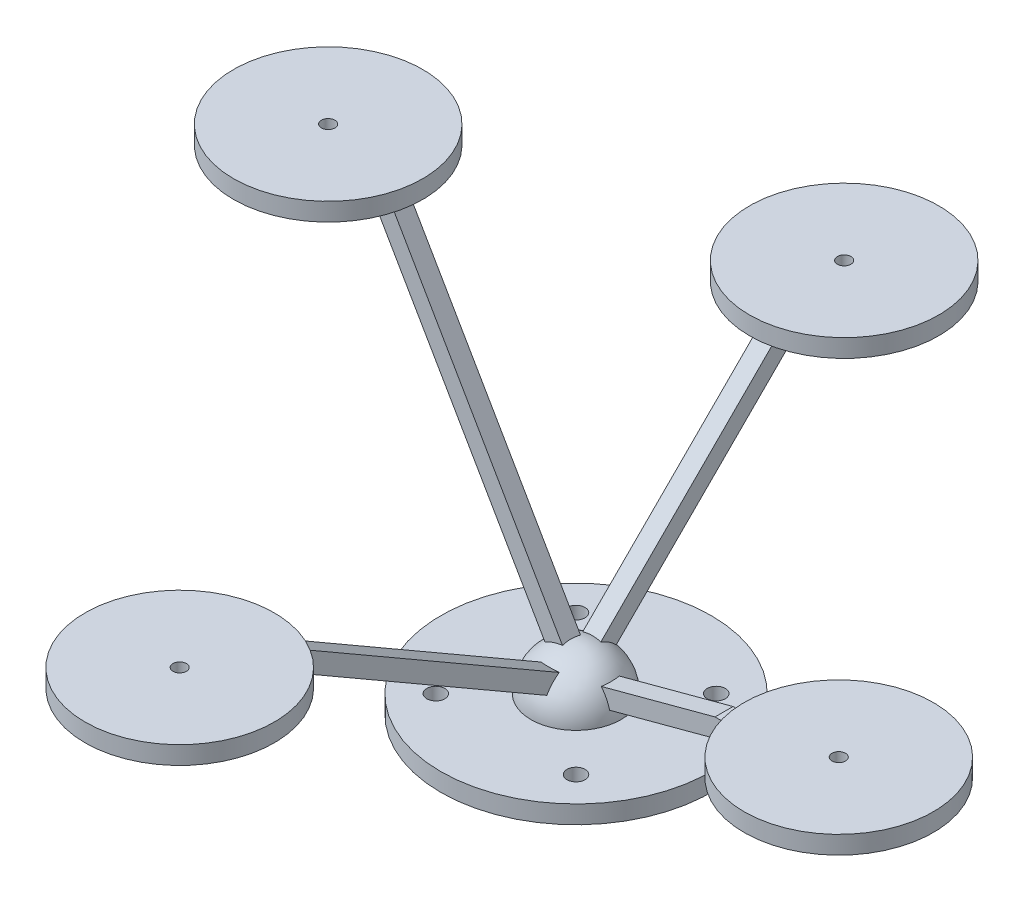
SolidWorks part; units mm, degrees
ref_plane "前视基准面" through (0, 0, 0) normal (0, 0, 1) x (1, 0, 0)
ref_plane "上视基准面" through (0, 0, 0) normal (0, 1, 0) x (1, 0, 0)
ref_plane "右视基准面" through (0, 0, 0) normal (1, 0, 0) x (0, 0, -1)
sketch "草图1" plane through (0, 0, 0) normal (0, 1, 0) x (1, 0, 0)
  line L0 (-23.4221, 0) -> (25.8766, 0) construction
  line L1 (0, 26.1921) -> (0, -25.0701) construction
  line L2 (-18.9498, 18.9498) -> (18.8862, -18.8862) construction
  line L3 (18.9424, 18.9424) -> (-20.2044, -20.2044) construction
  circle A0 centre (0, 0) radius 15
  circle A1 centre (0, 0) radius 11 construction
  circle A2 centre (7.7782, 7.7782) radius 1
  circle A3 centre (-7.7782, 7.7782) radius 1
  circle A4 centre (-7.7782, -7.7782) radius 1
  circle A5 centre (7.7782, -7.7782) radius 1
  dimension "D1" = 30
  dimension "D4" = 22
  dimension "D5" = 2
  dimension "D2" = 45
  dimension "D3" = 45
extrude "凸台-拉伸1" add sketch "草图1" along normal blind 2
sketch "草图2" plane through (0, 0, 0) normal (1, 0, 0) x (0, 0, -1)
  line L0 (0, 2) -> (0, 7)
  line L1 (15, 2) -> (-15, 2) construction
  line L2 (0, 2) -> (5, 2)
  arc A0 (0, 7) -> (5, 2) centre (0, 2) cw
  dimension "D1" = 5
revolve "旋转1" add sketch "草图2" angle 360 about L0
sketch "草图3" plane through (0, 0, 0) normal (0, 0, 1) x (1, 0, 0)
  line L0 (0, 2) -> (0, 9.7216) construction
  line L1 (15, 2) -> (-15, 2) construction
  line L2 (0, 2) -> (24.1481, 8.4705)
  line L3 (8.7782, 2) -> (6.7782, 2) construction
  line L4 (0, 4.0706) -> (16.4207, 8.4705)
  line L6 (16.4207, 8.4705) -> (24.1481, 8.4705)
  line L7 (0, 2) -> (-22.5, 40.9711)
  line L8 (-20.1906, 40.9711) -> (0, 6)
  line L9 (0, 6) -> (0, 4.0706)
  line L10 (-22.5, 40.9711) -> (-20.1906, 40.9711)
  dimension "D1" = 15
  dimension "D2" = 25
  dimension "D3" = 2
  dimension "D4" = 60
  dimension "D5" = 45
  dimension "D6" = 2
extrude "凸台-拉伸2" add sketch "草图3" along normal mid plane 2
sketch "草图4" plane through (0, 8.4705, 0) normal (0, 1, 0) x (1, 0, 0)
  line L0 (24.1481, -1) -> (24.1481, 1) construction
  circle A0 centre (29.1481, 0) radius 10.5
  circle A1 centre (29.1481, 0) radius 0.75
  dimension "D1" = 21
  dimension "D2" = 1.5
  dimension "D3" = 5
extrude "凸台-拉伸3" add sketch "草图4" along normal blind 2
sketch "草图5" plane through (0, 40.9711, 0) normal (0, 1, 0) x (1, 0, 0)
  line L0 (-22.5, -1) -> (-22.5, 1) construction
  circle A0 centre (-27.5, 0) radius 10.5
  circle A1 centre (-27.5, 0) radius 0.75
  dimension "D1" = 21
  dimension "D2" = 1.5
  dimension "D3" = 5
extrude "凸台-拉伸4" add sketch "草图5" along normal blind 2
sketch "草图6" plane through (0, 0, 0) normal (1, 0, 0) x (0, 0, -1)
  line L0 (0, 0) -> (0, 10.6928) construction
  line L1 (0, 2) -> (24.7487, 26.7487)
  line L2 (15, 2) -> (-15, 2) construction
  line L3 (8.7782, 2) -> (6.7782, 2) construction
  line L4 (0, 4.8284) -> (21.9203, 26.7487)
  line L5 (21.9203, 26.7487) -> (24.7487, 26.7487)
  line L6 (0, 2) -> (-38.9711, 24.5)
  line L7 (0, 4.3094) -> (-34.9711, 24.5)
  line L8 (-38.9711, 24.5) -> (-34.9711, 24.5)
  line L9 (0, 4.3094) -> (0, 4.8284)
  dimension "D1" = 45
  dimension "D2" = 35
  dimension "D3" = 2
  dimension "D4" = 30
  dimension "D5" = 45
  dimension "D6" = 2
extrude "凸台-拉伸5" add sketch "草图6" along normal mid plane 2
sketch "草图7" plane through (0, 26.7487, 0) normal (0, 1, 0) x (1, 0, 0)
  line L0 (1, 24.7487) -> (-1, 24.7487) construction
  circle A0 centre (0, 29.7487) radius 10.5
  circle A1 centre (0, 29.7487) radius 0.75
  dimension "D1" = 21
  dimension "D2" = 1.5
  dimension "D3" = 5
extrude "凸台-拉伸6" add sketch "草图7" along normal blind 2
sketch "草图8" plane through (0, 24.5, 0) normal (0, 1, 0) x (1, 0, 0)
  line L0 (1, -38.9711) -> (-1, -38.9711) construction
  circle A0 centre (0, -43.9711) radius 10.5
  circle A1 centre (0, -43.9711) radius 0.75
  dimension "D1" = 1.5
  dimension "D2" = 21
  dimension "D3" = 5
extrude "凸台-拉伸7" add sketch "草图8" along normal blind 2
